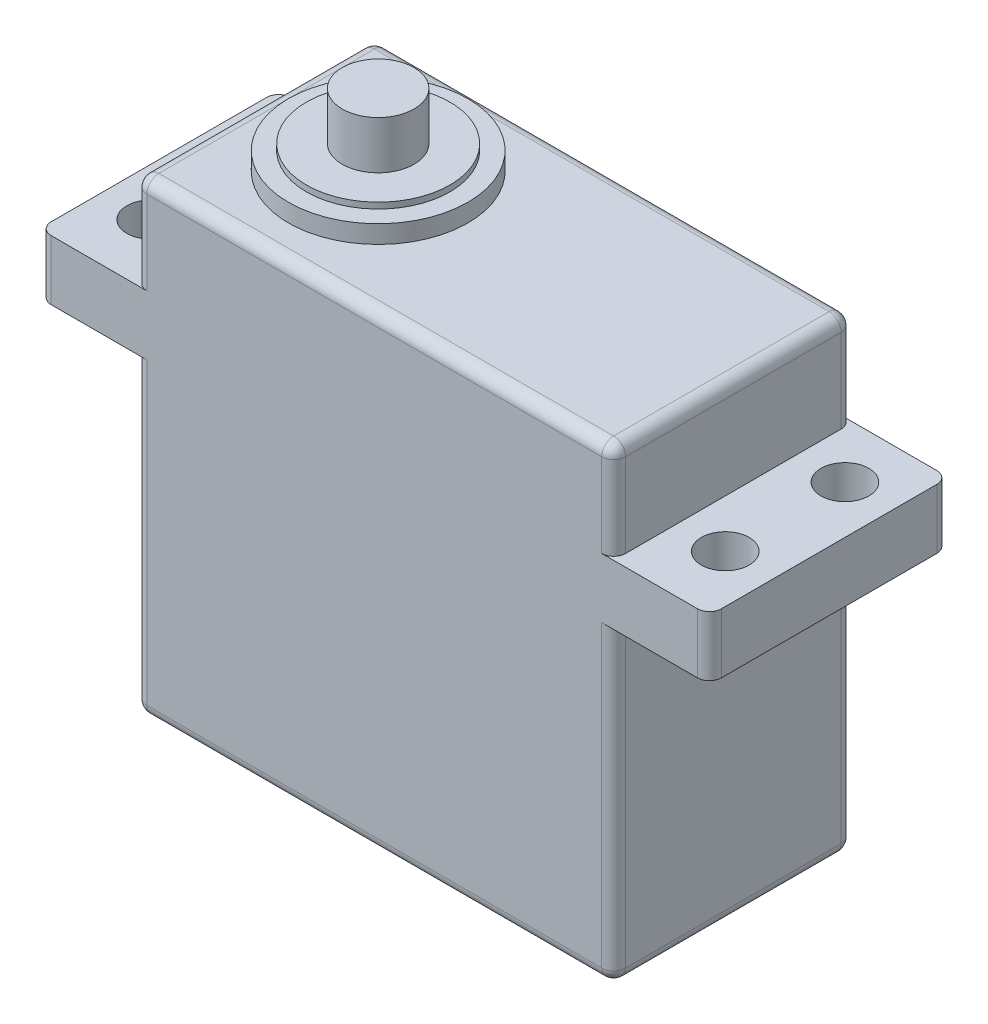
SolidWorks part; units mm, degrees
ref_plane "前视基准面" through (0, 0, 0) normal (0, 0, 1) x (1, 0, 0)
ref_plane "上视基准面" through (0, 0, 0) normal (0, 1, 0) x (1, 0, 0)
ref_plane "右视基准面" through (0, 0, 0) normal (1, 0, 0) x (0, 0, -1)
other "Configuration Table"
sketch "草图1" plane through (0, 0, 0) normal (0, 0, 1) x (1, 0, 0)
  line L1 (-20, 19.5) -> (20, 19.5)
  line L2 (-20, 19.5) -> (-20, -19.5)
  line L3 (-20, -19.5) -> (20, -19.5)
  line L4 (20, 19.5) -> (20, -19.5)
  line L5 (-20, 19.5) -> (20, -19.5) construction
  line L6 (-20, -19.5) -> (20, 19.5) construction
  point P0 (0, 0)
  dimension "D1" = 40
  dimension "D2" = 39
extrude "凸台-拉伸1" add sketch "草图1" along normal blind 20
sketch "草图2" plane through (20, 0, 0) normal (1, 0, 0) x (0, 0, -1)
  line L0 (-20, -19.5) -> (-20, 19.5) construction
  line L1 (-20, 11.5) -> (0, 11.5)
  line L2 (-20, 11.5) -> (-20, 6.5)
  line L3 (-20, 6.5) -> (0, 6.5)
  line L4 (0, 11.5) -> (0, 6.5)
  line L5 (0, -19.5) -> (0, 19.5) construction
  line L6 (-20, -19.5) -> (0, -19.5) construction
  dimension "D1" = 31
  dimension "D2" = 5
extrude "凸台-拉伸2" add sketch "草图2" along normal blind 8
sketch "草图3" plane through (0, 11.5, 0) normal (0, 1, 0) x (1, 0, 0)
  line L0 (11.7572, -9.6789) -> (31.4628, -9.6789) construction
  circle A0 centre (24, -4.6789) radius 2
  circle A1 centre (24, -14.6789) radius 2
  dimension "D1" = 4
  dimension "D2" = 24
  dimension "D3" = 10
extrude "切除-拉伸1" cut sketch "草图3" against normal blind 8
mirror "镜向1" about plane through (0, 0, 0) normal (1, 0, 0) of "凸台-拉伸2", "切除-拉伸1"
sketch "草图4" plane through (0, 19.5, 0) normal (0, 1, 0) x (1, 0, 0)
  line L0 (11.7572, -9.6789) -> (31.4628, -9.6789) construction
  line L1 (11.7572, -9.6789) -> (31.4628, -9.6789)
  circle A0 centre (-10, -9.6789) radius 7.5
  point P5 (0, 0)
  dimension "D1" = 34
  dimension "D2" = 15
extrude "凸台-拉伸3" add sketch "草图4" along normal blind 1.5 contours A0
sketch "草图5" plane through (0, 21, 0) normal (0, 1, 0) x (1, 0, 0)
  circle A0 centre (-10, -9.6789) radius 6
  circle A1 centre (-10, -9.6789) radius 7.5 construction
  circle A2 centre (-10, -9.6789) radius 7.5
  dimension "D1" = 12
extrude "凸台-拉伸4" add sketch "草图5" along normal blind 0.5 contours A0
sketch "草图6" plane through (0, 21.5, 0) normal (0, 1, 0) x (1, 0, 0)
  circle A0 centre (-10, -9.6789) radius 3
  circle A1 centre (-10, -9.6789) radius 6 construction
  circle A2 centre (-10, -9.6789) radius 6
  dimension "D1" = 6
extrude "凸台-拉伸5" add sketch "草图6" along normal blind 4 contours A0
fillet "圆角1" radius 1 20 edges at (-20, -19.5, 10) (20, -19.5, 10) (0, -19.5, 0) (0, -19.5, 20) (-20, -6.5, 20) (-20, -6.5, 0) (-28, 9, 20) (-28, 9, 0) (-20, 15.5, 20) (-20, 15.5, 0) (0, 19.5, 0) (0, 19.5, 20) (20, 15.5, 20) (20, 15.5, 0) (28, 9, 20) (20, -6.5, 20) (20, -6.5, 0) (28, 9, 0) (20, 19.5, 10) (-20, 19.5, 10)
